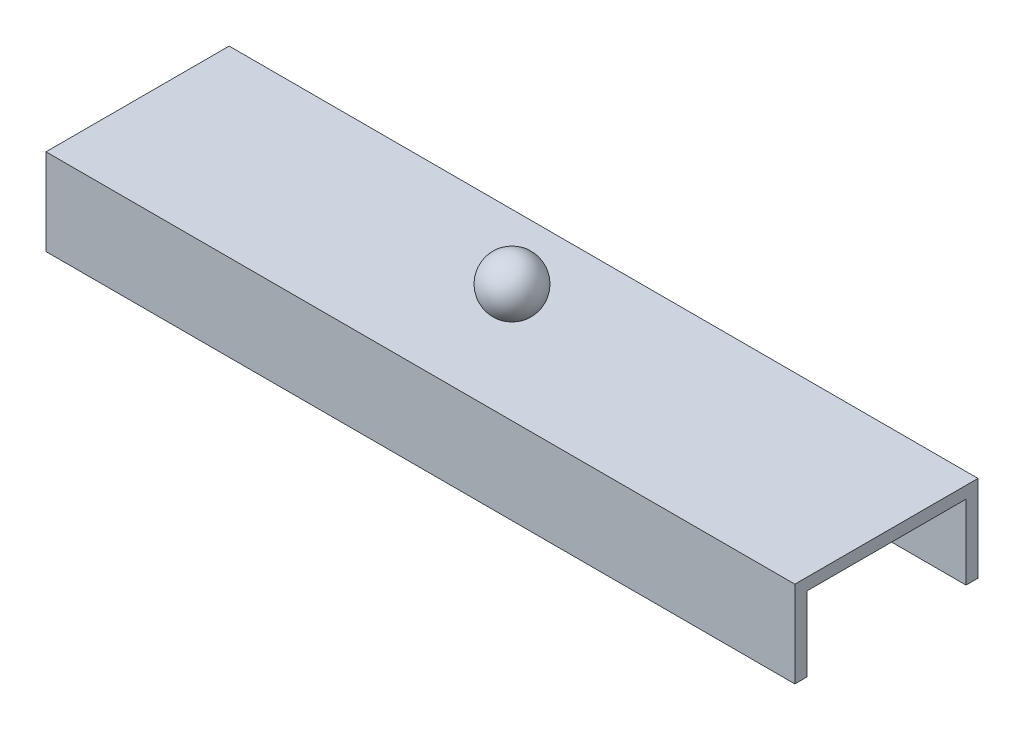
SolidWorks part; units mm, degrees
ref_plane "Plano frontal" through (0, 0, 0) normal (0, 0, 1) x (1, 0, 0)
ref_plane "Plano superior" through (0, 0, 0) normal (0, 1, 0) x (1, 0, 0)
ref_plane "Plano direito" through (0, 0, 0) normal (1, 0, 0) x (0, 0, -1)
sketch "Esboço3" plane through (0, 0, 0) normal (0, 0, 1) x (1, 0, 0)
  line L0 (0, 0) -> (0, 9)
  arc A0 (0, 9) -> (0, 0) centre (0, 4.5) ccw
  dimension "D1" = 9
revolve "Revolução1" add sketch "Esboço3" angle 360 about L0
sketch "Esboço4" plane through (0, 0, 0) normal (0, 1, 0) x (1, 0, 0)
  line L1 (-62.6, 13.31) -> (62.6, 13.31)
  line L2 (-62.6, 13.31) -> (-62.6, -13.31)
  line L3 (-62.6, -13.31) -> (62.6, -13.31)
  line L4 (62.6, 13.31) -> (62.6, -13.31)
  dimension "D1" = 26.62
  dimension "D2" = 125.2
  dimension "D3" = 62.6
  dimension "D4" = 13.31
extrude "Ressalto-extrusão1" add sketch "Esboço4" against normal blind 2 separate body
sketch "Esboço5" plane through (0, 0, 0) normal (0, 0, 1) x (1, 0, 0)
  line L1 (-62.6, 0) -> (62.6, 0)
  line L2 (-62.6, 0) -> (-62.6, -14.45)
  line L3 (-62.6, -14.45) -> (62.6, -14.45)
  line L4 (62.6, 0) -> (62.6, -14.45)
  point P5 (0, 0)
  dimension "D1" = 125.2
  dimension "D2" = 14.45
extrude "Ressalto-extrusão2" add sketch "Esboço5" along normal blind 2 from surface at 13.31 starting at face at (0, -1, 13.31)
sketch "Esboço6" plane through (0, 0, 0) normal (0, 0, 1) x (1, 0, 0)
  line L0 (62.6, -14.45) -> (-62.6, -14.45) construction
  line L1 (-62.6, 0) -> (62.6, 0)
  line L2 (-62.6, 0) -> (-62.6, -14.45)
  line L3 (-62.6, -14.45) -> (62.6, -14.45)
  line L4 (62.6, 0) -> (62.6, -14.45)
  dimension "D1" = 125.2
extrude "Ressalto-extrusão3" add sketch "Esboço6" against normal blind 2 from surface at -13.31 starting at face at (0, -1, -13.31)
